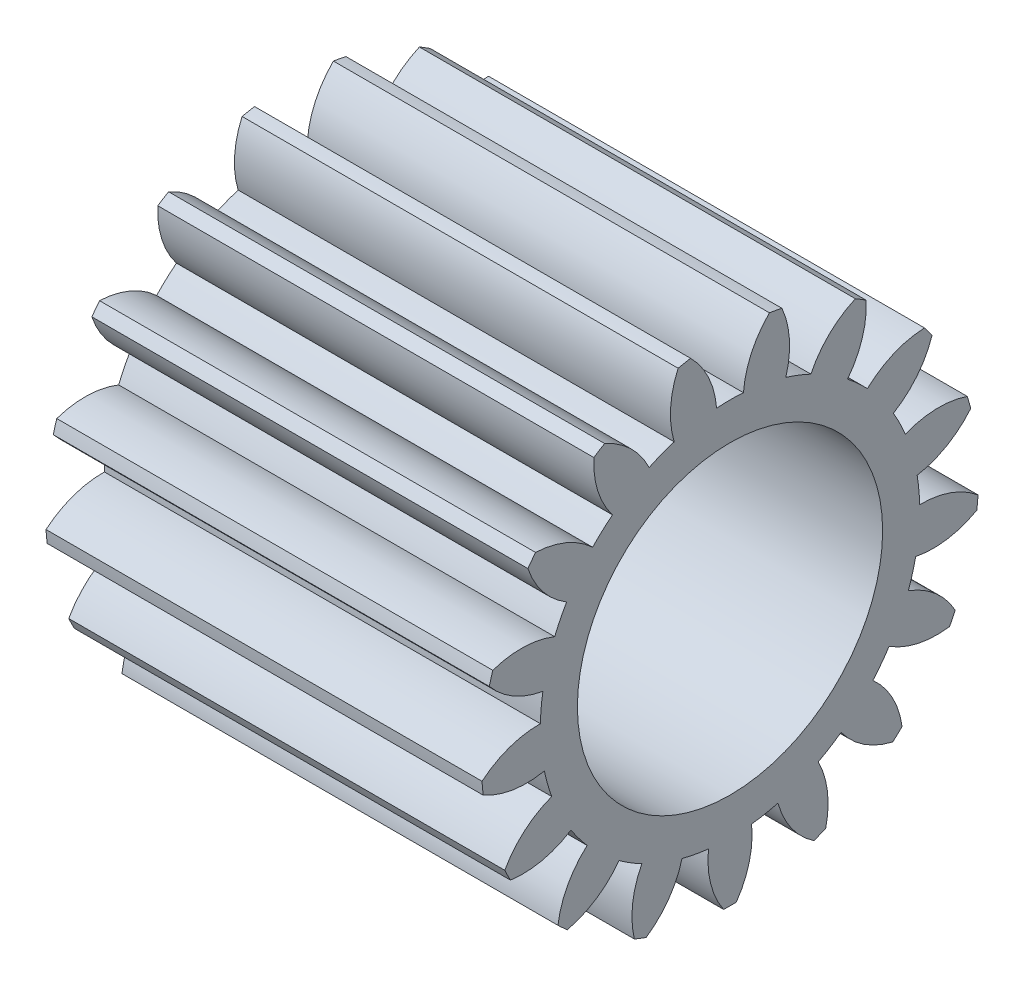
SolidWorks part; units mm, degrees
ref_plane "Plane1" through (0, 0, 0) normal (0, 0, 1) x (1, 0, 0)
ref_plane "Plane2" through (0, 0, 0) normal (0, 1, 0) x (1, 0, 0)
ref_plane "Plane3" through (0, 0, 0) normal (1, 0, 0) x (0, 0, -1)
other "Configuration Table"
sketch "HoldingSke" plane through (0, 0, 0) normal (0, 1, 0) x (1, 0, 0)
  line L0 (0, 0) -> (0.3188, -0.0975)
  line L1 (-15, 0) -> (100, 0) construction
  line L2 (0, 0) -> (-2.1039, 2.3779)
  line L3 (0, 0) -> (-11.863, 4.5341)
  line L4 (0, 0) -> (8.2586, 2.5249)
  line L5 (0, 0) -> (-46.8476, -17.4728)
  line L6 (0, 0) -> (-41.4481, -27.9652)
  line L7 (-2.1039, 2.3779) -> (8.6586, 51.2059)
  line L8 (-76.2, 54.61) -> (-72.9, 54.61)
  line L9 (-71.009, 38.7566) -> (-53.1078, 45.2721)
  line L10 (-76.2, 71.12) -> (104.1128, 71.12)
  line L11 (0, 0) -> (-50, 0)
  line L12 (-76.2, 101.6) -> (-76.093, 101.6)
  line L13 (24.9733, 27.94) -> (52.9518, 28.4284)
  line L14 (24.9733, 27.94) -> (24.9743, 27.94)
  line L15 (24.9733, 27.94) -> (100.4006, 29.5858)
  line L16 (-63.627, -3) -> (-12.827, -3)
  circle A0 centre (0, 0) radius 17.5
  circle A1 centre (0, 0) radius 21.749
  circle A2 centre (0, 0) radius 37.5
  circle A3 centre (0, 0) radius 17.5
  dimension "MHD" = 43.498
  dimension "Hub_dia" = 75
  dimension "Bore" = 35
  dimension "MBD" = 35
  dimension "Num_teeth" = 17
  dimension "Pitch" = 0.3333
  dimension "Overall_len" = 50
  dimension "Show_teeth" = 17
  dimension "Thickness" = 50
  dimension "OAL" = 50.0001
  dimension "T_dim" = 3.3
  dimension "Ap" = 20
  dimension "H" = 19.05
  dimension "Pitch_radius" = 180.3128
  dimension "Width" = 50
  dimension "Backlash" = 0.107
  dimension "Addendum_fac" = 1
  dimension "Dedendum_fac" = 1.25
  dimension "Clearance_fac" = 0.25
  dimension "Dedendum_add" = 0.001
  dimension "Module" = 3
sketch "BasProSke" plane through (0, 0, 0) normal (0, 1, 0) x (1, 0, 0)
  line L0 (-10, 0) -> (60, 0) construction
  line L1 (0, 0) -> (0, 28.5)
  line L2 (0, 0) -> (50, 0)
  line L3 (50, 0) -> (50, 28.5)
  line L4 (50, 28.5) -> (0, 28.5)
  dimension "Thickness" = 50
  dimension "Diameter" = 57
revolve "Base-Revolve" add sketch "BasProSke" angle 360 about L0
sketch "TooCutSke" plane through (0, 0, 0) normal (1, 0, 0) x (0, 0, -1)
  line L1 (0, 0) -> (0, 107) construction
  line L2 (0, 0) -> (-2.54, 25.3732) construction
  line L3 (0, 0) -> (-9.3374, 49.9505) construction
  line L4 (-2.54, 25.3732) -> (-4.6687, 24.9753) construction
  arc A0 (1.5403, 21.6944) -> (-1.5403, 21.6944) centre (0, 0) ccw
  arc A1 (4.5406, 28.1617) -> (-4.5406, 28.1617) centre (0, 0) ccw
  circle A2 centre (0, 0) radius 25.5 construction
  circle A3 centre (0, 0) radius 23.9622 construction
  arc A4 (-1.5403, 21.6944) -> (-4.5406, 28.1617) centre (-11.7098, 20.9061) ccw
  arc A5 (4.5406, 28.1617) -> (1.5403, 21.6944) centre (11.7098, 20.9061) ccw
  dimension "Root_dia" = 43.498
  dimension "Overcut_dia" = 57.0508
  dimension "Pitch_dia" = 51
  dimension "Base_dia" = 47.9243
  dimension "Flank_rad" = 10.2
  dimension "Half_ang" = 10.588
  dimension "Half_CT" = 2.1656
extrude "ToothCut" cut sketch "TooCutSke" along normal through all
fillet "Breaks" [suppressed] radius 0.06
fillet "RootFillets" [suppressed] radius 0.751
pattern_circular "TeethCuts" count 17 every 21.176 about axis through (-10, 0, 0) along (1, 0, 0) of "ToothCut", "RootFillets", "Breaks"
sketch "HubNeaOneSke" plane through (0, 0, 0) normal (-1, 0, 0) x (0, 0, 1)
  circle A0 centre (0, 0) radius 21.749
  dimension "Diameter" = 43.498
extrude "HubNearOne" [suppressed] add sketch "HubNeaOneSke" along normal blind 10.0001
sketch "HubNeaBotSke" plane through (0, 0, 0) normal (-1, 0, 0) x (0, 0, 1)
  circle A0 centre (0, 0) radius 21.749
  dimension "Diameter" = 43.498
extrude "HubNearBoth" [suppressed] add sketch "HubNeaBotSke" along normal blind 5
ref_plane "FarPln" through (50, 0, 0) normal (1, 0, 0) x (0, 0, -1)
sketch "HubFarSke" plane through (50, 0, 0) normal (1, 0, 0) x (0, 0, -1)
  circle A0 centre (0, 0) radius 21.749
  dimension "Diameter" = 43.498
extrude "HubFar" [suppressed] add sketch "HubFarSke" along normal blind 5
sketch "BorSke" plane through (0, 0, 0) normal (1, 0, 0) x (0, 0, -1)
  circle A0 centre (0, 0) radius 17.5
  dimension "Diameter" = 35
extrude "Bore" cut sketch "BorSke" along normal mid plane 100.0001
sketch "KeySke" plane through (0, 0, 0) normal (1, 0, 0) x (0, 0, -1)
  line L0 (-5, 0) -> (-5, 20.8)
  line L1 (-5, 20.8) -> (5, 20.8)
  line L2 (5, 20.8) -> (5, 0)
  line L3 (0, 0) -> (0, 34) construction
  line L4 (-5, 0) -> (5, 0)
  dimension "Offset" = 20.8
  dimension "Width" = 10
extrude "Keyway" [suppressed] cut sketch "KeySke" along normal mid plane 100.0001
pattern_circular "Keyway2" [suppressed] count 2 every 90 about axis through (-10, 0, 0) along (1, 0, 0)
equation "' \"Module@HoldingSke\" = 6.35"
equation "' \"Num_teeth@HoldingSke\" = 12"
equation "' \"Ap@HoldingSke\" =  20"
equation "' \"Ap@HoldingSke\" = 20"
equation "' \"Width@HoldingSke\" = 0.5 * 25.4"
equation "' \"Hub_dia@HoldingSke\"= 1 * 25.4"
equation "' \"Hub_dia@HoldingSke\" = 1 * 25.4"
equation "' \"Overall_len@HoldingSke\" = 1.0 * 25.4"
equation "' \"Bore@HoldingSke\" = 0.75 * 25.4"
equation "' \"T_dim@HoldingSke\" = 0.1 * 25.4"
equation "' \"Width@KeySke\" = 0.25 * 25.4"
equation "' \"Show_teeth@HoldingSke\" = 13"
equation "' \"Backlash@HoldingSke\" = 0.009 * 25.4"
equation "' \"Addendum_fac@HoldingSke\" = 1.0"
equation "' \"Dedendum_fac@HoldingSke\" = 1.25"
equation "' \"Dedendum_add@HoldingSke\" = 0.00005 * 25.4"
equation "' \"Clearance_fac@HoldingSke\" = 0.25"
equation "\"Pitch@HoldingSke\" = 1 / \"Module@HoldingSke\""
equation "\"Overcut_dia@TooCutSke\" = (\"Num_teeth@HoldingSke\" + 2 * \"Addendum_fac@HoldingSke\") / \"Pitch@HoldingSke\" + 0.002 * 25.4"
equation "\"Pitch_dia@TooCutSke\" = \"Num_teeth@HoldingSke\" / \"Pitch@HoldingSke\""
equation "\"Base_dia@TooCutSke\" = \"Num_teeth@HoldingSke\" / \"Pitch@HoldingSke\" * cos((\"Ap@HoldingSke\"  * 3.14159265 / 180))"
equation "\"Root_dia@TooCutSke\" = (\"Num_teeth@HoldingSke\" + 2) / \"Pitch@HoldingSke\" - 2 * (\"Addendum_fac@HoldingSke\" + \"Dedendum_fac@HoldingSke\") / \"Pitch@HoldingSke\" - \"Dedendum_add@HoldingSke\" * 2"
equation "\"Half_ang@TooCutSke\" = 180 / \"Num_teeth@HoldingSke\""
equation "\"Half_CT@TooCutSke\" = \"Num_teeth@HoldingSke\" / \"Pitch@HoldingSke\" * sin((3.14159265 / 2 / \"Num_teeth@HoldingSke\")) / 2 - 7 * \"Backlash@HoldingSke\" / 4"
equation "\"Flank_rad@TooCutSke\" = \"Num_teeth@HoldingSke\" / \"Pitch@HoldingSke\" / 5"
equation "\"Radius@RootFillets\" = \"Clearance_fac@HoldingSke\" / \"Pitch@HoldingSke\" + \"Dedendum_add@HoldingSke\""
equation "\"Break_rad@Breaks\" = 0.02 / \"Pitch@HoldingSke\""
equation "\"Thickness@HoldingSke\" = \"Width@HoldingSke\""
equation "\"OAL@HoldingSke\" = \"Thickness@HoldingSke\""
equation "\"MHD@HoldingSke\" = (\"Num_teeth@HoldingSke\" + 2) / \"Pitch@HoldingSke\" - 2 * (\"Addendum_fac@HoldingSke\" + \"Dedendum_fac@HoldingSke\")  / \"Pitch@HoldingSke\" - \"Dedendum_add@HoldingSke\" * 2"
equation "\"MBD@HoldingSke\" = (\"Num_teeth@HoldingSke\" + 2) / \"Pitch@HoldingSke\" - 2 * (\"Addendum_fac@HoldingSke\" + \"Dedendum_fac@HoldingSke\")  / \"Pitch@HoldingSke\" - \"Dedendum_add@HoldingSke\" * 2 - 0.002 * 25.4"
equation "\"MHD@HoldingSke\" = ((sgn( \"MHD@HoldingSke\" - \"Hub_dia@HoldingSke\" )-1)*( \"MHD@HoldingSke\" - \"Hub_dia@HoldingSke\" ))/-2+ \"Hub_dia@HoldingSke\""
equation "\"MBD@HoldingSke\" = ((sgn( \"MBD@HoldingSke\" - \"Bore@HoldingSke\" )-1)*( \"MBD@HoldingSke\" - \"Bore@HoldingSke\" ))/-2+ \"Bore@HoldingSke\""
equation "\"OAL@HoldingSke\" = ((sgn( \"OAL@HoldingSke\" - \"Overall_len@HoldingSke\" )+1)*( \"OAL@HoldingSke\" - \"Overall_len@HoldingSke\" ))/2 + \"Overall_len@HoldingSke\" + 0.000002 * 25.4"
equation "\"Num_teeth@TeethCuts\" = int( \"Show_teeth@HoldingSke\" ) + 1"
equation "\"Num_teeth@TeethCuts\" = ((sgn( \"Num_teeth@TeethCuts\" - \"Num_teeth@HoldingSke\" )-1)*( \"Num_teeth@TeethCuts\" - \"Num_teeth@HoldingSke\" ))/-2+ \"Num_teeth@HoldingSke\""
equation "\"Num_teeth@TeethCuts\" = ((sgn( \"Num_teeth@TeethCuts\" - 2.0)+1)*( \"Num_teeth@TeethCuts\" - 2.0))/2 +2.0"
equation "\"Angle@TeethCuts\" = 360.0 / \"Num_teeth@HoldingSke\""
equation "\"Diameter@BasProSke\" = (\"Num_teeth@HoldingSke\" + 2 * \"Addendum_fac@HoldingSke\") / \"Pitch@HoldingSke\""
equation "\"Thickness@BasProSke\"  = \"Thickness@HoldingSke\""
equation "' \"Fillet_rad@BasProSke\" =  \"Thickness@HoldingSke\" * 0.05"
equation "' \"Fillet_rad@BasProSke\" = \"Thickness@HoldingSke\" * 0.05"
equation "\"MHD@HoldingSke\" = ((sgn( \"MHD@HoldingSke\" - \"Root_dia@TooCutSke\" )-1)*( \"MHD@HoldingSke\" - \"Root_dia@TooCutSke\" ))/-2+ \"Root_dia@TooCutSke\""
equation "\"Diameter@HubNeaOneSke\" = \"MHD@HoldingSke\""
equation "\"Length@HubNearOne\" = \"OAL@HoldingSke\" - \"Thickness@BasProSke\""
equation "\"Diameter@HubNeaBotSke\" = \"MHD@HoldingSke\""
equation "\"Length@HubNearBoth\" = ( \"OAL@HoldingSke\" - \"Thickness@BasProSke\" ) / 2.0"
equation "\"Thickness@FarPln\" = \"Thickness@BasProSke\""
equation "\"Diameter@HubFarSke\" = \"MHD@HoldingSke\""
equation "\"Length@HubFar\" = ( \"OAL@HoldingSke\" - \"Thickness@BasProSke\" ) / 2.0"
equation "\"Diameter@BorSke\" = \"MBD@HoldingSke\""
equation "\"D1@Bore\" = \"OAL@HoldingSke\" * 2.0"
equation "\"D1@Keyway\" = \"OAL@HoldingSke\" * 2.0"
equation "\"Offset@KeySke\" = \"T_dim@HoldingSke\" + \"MBD@HoldingSke\" / 2.0"
